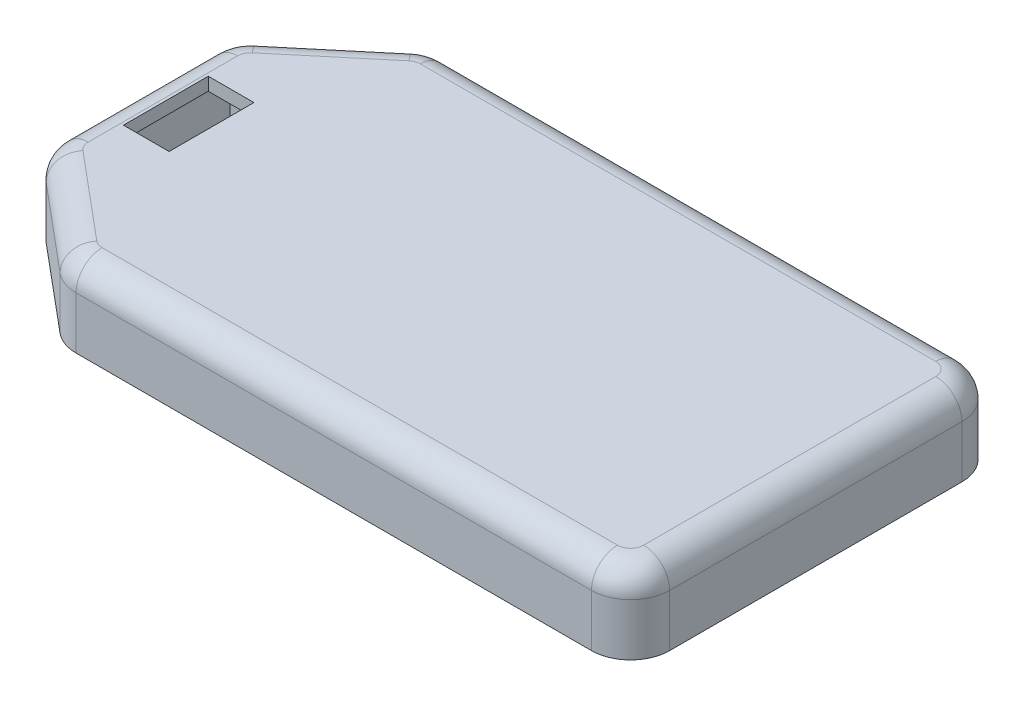
SolidWorks part; units mm, degrees
ref_plane "Front Plane" through (0, 0, 0) normal (0, 0, 1) x (1, 0, 0)
ref_plane "Top Plane" through (0, 0, 0) normal (0, 1, 0) x (1, 0, 0)
ref_plane "Right Plane" through (0, 0, 0) normal (1, 0, 0) x (0, 0, -1)
sketch "Sketch1" plane through (0, 0, 0) normal (0, 1, 0) x (1, 0, 0)
  line L61 (26.7755, -17.8683) -> (26.7755, 4.5317)
  line L65 (25.2755, 6.0317) -> (25.2755, -19.3683) construction
  line L68 (25.2755, -19.3683) -> (-15.3245, -19.3683) construction
  line L69 (-15.3245, -19.3683) -> (-15.3245, 6.0317) construction
  line L70 (-15.3245, 6.0317) -> (25.2755, 6.0317) construction
  line L73 (-17.6603, 6.8319) -> (-24.2004, 1.356)
  line L74 (-25.2745, -0.9442) -> (-25.2745, -12.3924)
  line L75 (-24.2004, -14.6926) -> (-17.6603, -20.1685)
  line L76 (-15.3245, -19.3683) -> (25.2755, 6.0317) construction
  line L77 (25.2755, -19.3683) -> (-15.3245, 6.0317) construction
  line L78 (-18.3245, -0.5433) -> (-18.3245, -12.7933) construction
  line L79 (-24.2745, -0.5433) -> (-18.3245, -0.5433) construction
  line L80 (-24.2745, -12.7933) -> (-24.2745, -0.5433) construction
  line L81 (-18.3245, -12.7933) -> (-24.2745, -12.7933) construction
  line L82 (-24.2745, -12.7933) -> (-18.3245, -0.5433) construction
  line L83 (-18.3245, -12.7933) -> (-24.2745, -0.5433) construction
  line L84 (-21.2995, -6.6683) -> (4.9755, -6.6683) construction
  line L87 (-15.7344, -17.8683) -> (-15.7344, 4.5317) construction
  line L88 (-15.7344, 4.5317) -> (23.7755, 4.5317) construction
  line L89 (23.7755, 4.5317) -> (23.7755, -17.8683) construction
  line L90 (23.7755, -17.8683) -> (-15.7344, -17.8683) construction
  line L91 (-15.7344, 7.5317) -> (23.7755, 7.5317)
  line L92 (-15.7344, -20.8683) -> (23.7755, -20.8683)
  arc A18 (23.7755, -20.8683) -> (26.7755, -17.8683) centre (23.7755, -17.8683) ccw
  arc A19 (26.7755, 4.5317) -> (23.7755, 7.5317) centre (23.7755, 4.5317) ccw
  arc A20 (-15.7344, 7.5317) -> (-17.6603, 6.8319) centre (-15.7344, 4.5317) ccw
  arc A21 (-24.2004, 1.356) -> (-25.2745, -0.9442) centre (-22.2745, -0.9442) ccw
  arc A22 (-25.2745, -12.3924) -> (-24.2004, -14.6926) centre (-22.2745, -12.3924) ccw
  arc A23 (-17.6603, -20.1685) -> (-15.7344, -20.8683) centre (-15.7344, -17.8683) ccw
  point P1 (0, 0)
  point P2 (4.9755, -6.6683)
  dimension "D11" = 3
  dimension "D2" = 52.05
  dimension "D3" = 1
  dimension "D4" = 5.95
  dimension "D5" = 12.25
  dimension "D6" = 25.4
  dimension "D7" = 3
  dimension "D8" = 1.5
extrude "Boss-Extrude1" add sketch "Sketch1" along normal blind 6
sketch "Sketch2" plane through (0, 0, 0) normal (0, 1, 0) x (1, 0, 0)
  line L0 (25.2755, 6.0317) -> (25.2755, -19.3683) construction
  line L1 (25.2755, -19.3683) -> (-15.3245, -19.3683) construction
  line L2 (-15.3245, -19.3683) -> (-15.3245, 6.0317) construction
  line L3 (-15.3245, 6.0317) -> (25.2755, 6.0317) construction
  line L4 (25.2755, 6.0317) -> (25.2755, -19.3683)
  line L5 (25.2755, -19.3683) -> (-15.3245, -19.3683)
  line L6 (-15.3245, -19.3683) -> (-15.3245, 6.0317)
  line L7 (-15.3245, 6.0317) -> (25.2755, 6.0317)
  line L8 (-18.3245, -12.7933) -> (-24.2745, -12.7933) construction
  line L9 (-18.3245, -0.5433) -> (-18.3245, -12.7933) construction
  line L10 (-24.2745, -0.5433) -> (-18.3245, -0.5433) construction
  line L11 (-24.2745, -12.7933) -> (-24.2745, -0.5433) construction
  line L12 (-18.3245, -12.7933) -> (-24.2745, -12.7933)
  line L13 (-18.3245, -0.5433) -> (-18.3245, -12.7933)
  line L14 (-24.2745, -0.5433) -> (-18.3245, -0.5433)
  line L15 (-24.2745, -12.7933) -> (-24.2745, -0.5433)
extrude "Cut-Extrude1" cut sketch "Sketch2" along normal blind 5
sketch "Sketch4" plane through (0, 6, 0) normal (0, 1, 0) x (1, 0, 0)
  line L1 (-23.0495, -9.9183) -> (-19.5495, -9.9183)
  line L2 (-23.0495, -9.9183) -> (-23.0495, -3.4183)
  line L3 (-23.0495, -3.4183) -> (-19.5495, -3.4183)
  line L4 (-19.5495, -9.9183) -> (-19.5495, -3.4183)
  line L5 (-23.0495, -9.9183) -> (-19.5495, -3.4183) construction
  line L6 (-23.0495, -3.4183) -> (-19.5495, -9.9183) construction
  point P0 (-21.2995, -6.6683)
  dimension "D1" = 6.5
  dimension "D2" = 3.5
extrude "Cut-Extrude2" cut sketch "Sketch4" against normal through all
fillet "Fillet1" radius 2 12 edges at (4.0206, 6, 20.8683) (-16.7589, 6, 20.6879) (-20.9303, 6, 17.4306) (-24.9927, 6, 13.6617) (-25.2745, 6, 6.6683) (-24.9927, 6, -0.3251) (-20.9303, 6, -4.094) (-16.7589, 6, -7.3513) (4.0206, 6, -7.5317) (25.8968, 6, -6.653) (26.7755, 6, 6.6683) (25.8968, 6, 19.9896)
